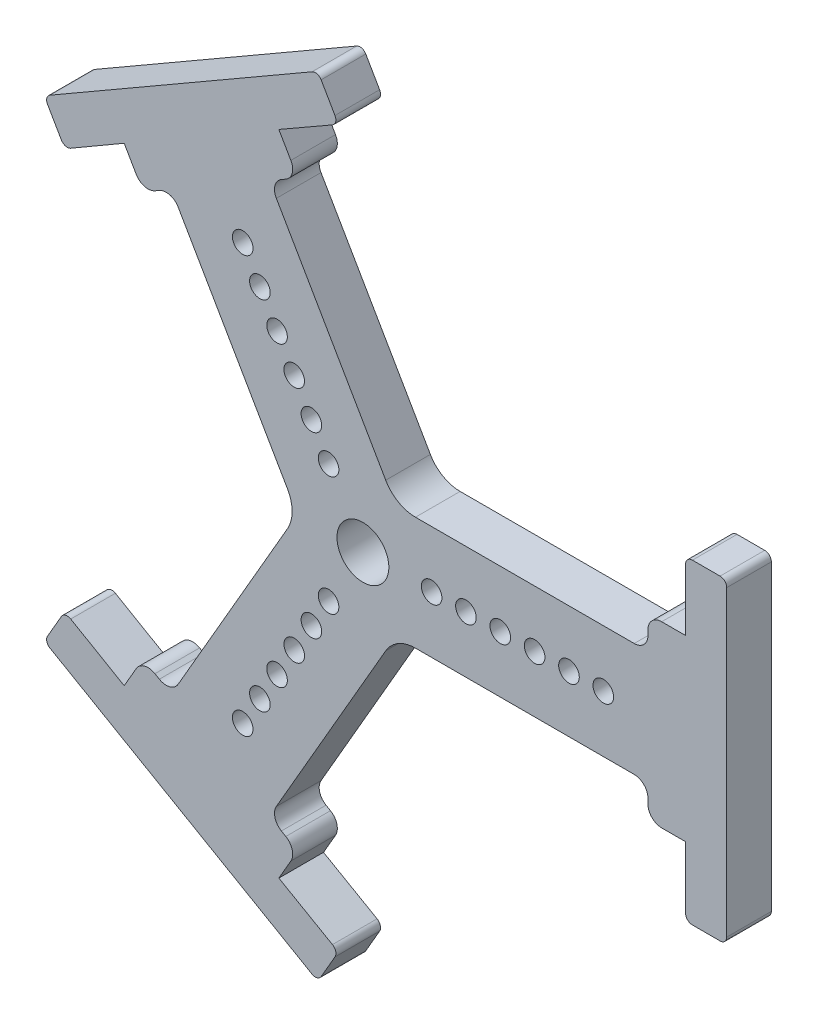
SolidWorks part; units mm, degrees
ref_plane "Plan de face" through (0, 0, 0) normal (0, 0, 1) x (1, 0, 0)
ref_plane "Plan de dessus" through (0, 0, 0) normal (0, 1, 0) x (1, 0, 0)
ref_plane "Plan de droite" through (0, 0, 0) normal (1, 0, 0) x (0, 0, -1)
sketch "Esquisse1" plane through (0, 0, 0) normal (0, 0, 1) x (1, 0, 0)
  line L0 (0, 0) -> (132.854, 0) construction
  line L1 (93.9876, -26) -> (93.9407, -43.9948)
  line L3 (95.9407, -46) -> (104, -46)
  line L4 (15.3045, 16.5081) -> (79, 16.5081)
  line L5 (83, 20.5081) -> (83, 22)
  line L6 (87, 26) -> (93.9876, 26)
  line L13 (87, -26) -> (93.9876, -26)
  line L19 (83, -20.5081) -> (83, -22)
  line L22 (15.3045, -16.5081) -> (79, -16.5081)
  line L28 (95.9407, 46) -> (104, 46)
  line L29 (105.9354, 44.0646) -> (105.9354, -44.0646)
  line L31 (93.9876, 26) -> (93.9407, 43.9948)
  line L32 (6.6442, -21.5081) -> (-25.2036, -76.6701)
  line L33 (-20.9833, -88.3442) -> (-24.4772, -94.3957)
  line L34 (-24.4772, -94.3957) -> (-8.8697, -103.3524)
  line L35 (-8.1332, -106.0871) -> (-12.1628, -113.0666)
  line L36 (-14.8067, -113.7751) -> (-91.1287, -69.7105)
  line L37 (-87.8075, -60.0871) -> (-91.8372, -67.0666)
  line L38 (-69.5105, -68.3957) -> (-85.0709, -59.3576)
  line L39 (-66.0167, -62.3442) -> (-69.5105, -68.3957)
  line L40 (-59.2605, -61.6261) -> (-60.5526, -60.8801)
  line L41 (-21.9486, -5) -> (-53.7964, -60.162)
  line L42 (-23.7395, -82.1342) -> (-22.4474, -82.8801)
  line L43 (-21.9486, 5) -> (-53.7964, 60.162)
  line L44 (-66.0167, 62.3442) -> (-69.5105, 68.3957)
  line L45 (-69.5105, 68.3957) -> (-85.0709, 59.3576)
  line L46 (-87.8075, 60.0871) -> (-91.8372, 67.0666)
  line L47 (-91.1287, 69.7105) -> (-14.8067, 113.7751)
  line L48 (-8.1332, 106.0871) -> (-12.1628, 113.0666)
  line L49 (-24.4772, 94.3957) -> (-8.8697, 103.3524)
  line L50 (-20.9833, 88.3442) -> (-24.4772, 94.3957)
  line L51 (-23.7395, 82.1342) -> (-22.4474, 82.8801)
  line L52 (6.6442, 21.5081) -> (-25.2036, 76.6701)
  line L53 (-59.2605, 61.6261) -> (-60.5526, 60.8801)
  circle A1 centre (0, 0) radius 7.55
  arc A3 (83, 22) -> (87, 26) centre (87, 22) cw
  arc A4 (79, 16.5081) -> (83, 20.5081) centre (79, 20.5081) ccw
  circle A15 centre (20, 0) radius 3
  circle A16 centre (40, 0) radius 3
  circle A17 centre (60, 0) radius 3
  circle A18 centre (70, 0) radius 3
  circle A19 centre (50, 0) radius 3
  circle A20 centre (30, 0) radius 3
  arc A33 (15.3045, 16.5081) -> (6.6442, 21.5081) centre (15.3045, 26.5081) cw
  arc A36 (95.9407, 46) -> (93.9407, 43.9948) centre (95.9407, 44) ccw
  arc A37 (105.9354, -44.0646) -> (104, -46) centre (104, -44.0646) cw
  arc A38 (95.9407, -46) -> (93.9407, -43.9948) centre (95.9407, -44) cw
  arc A39 (105.9354, 44.0646) -> (104, 46) centre (104, 44.0646) ccw
  arc A40 (79, -16.5081) -> (83, -20.5081) centre (79, -20.5081) cw
  arc A41 (83, -22) -> (87, -26) centre (87, -22) ccw
  arc A42 (15.3045, -16.5081) -> (6.6442, -21.5081) centre (15.3045, -26.5081) ccw
  arc A43 (6.6442, -21.5081) -> (15.3045, -16.5081) centre (15.3045, -26.5081) cw
  arc A44 (-25.2036, -76.6701) -> (-23.7395, -82.1342) centre (-21.7395, -78.6701) ccw
  arc A45 (-22.4474, -82.8801) -> (-20.9833, -88.3442) centre (-24.4474, -86.3442) cw
  arc A46 (-8.1332, -106.0871) -> (-8.8697, -103.3524) centre (-9.8652, -105.0871) ccw
  arc A47 (-14.8067, -113.7751) -> (-12.1628, -113.0666) centre (-13.839, -112.0989) ccw
  arc A48 (-60.5526, -60.8801) -> (-66.0167, -62.3442) centre (-62.5526, -64.3442) ccw
  arc A49 (-53.7964, -60.162) -> (-59.2605, -61.6261) centre (-57.2605, -58.162) cw
  circle A50 centre (-35, -60.6218) radius 3
  circle A51 centre (-30, -51.9615) radius 3
  circle A52 centre (-25, -43.3013) radius 3
  circle A53 centre (-15, -25.9808) radius 3
  circle A54 centre (-10, -17.3205) radius 3
  circle A55 centre (-20, -34.641) radius 3
  arc A56 (-21.9486, 5) -> (-21.9486, -5) centre (-30.6089, 0) cw
  arc A57 (-53.7964, 60.162) -> (-59.2605, 61.6261) centre (-57.2605, 58.162) ccw
  arc A58 (-60.5526, 60.8801) -> (-66.0167, 62.3442) centre (-62.5526, 64.3442) cw
  arc A59 (-87.8075, 60.0871) -> (-85.0709, 59.3576) centre (-86.0755, 61.0871) ccw
  arc A60 (-91.1287, 69.7105) -> (-91.8372, 67.0666) centre (-90.161, 68.0344) ccw
  arc A61 (-22.4474, 82.8801) -> (-20.9833, 88.3442) centre (-24.4474, 86.3442) ccw
  arc A62 (-25.2036, 76.6701) -> (-23.7395, 82.1342) centre (-21.7395, 78.6701) cw
  circle A63 centre (-35, 60.6218) radius 3
  circle A64 centre (-30, 51.9615) radius 3
  circle A65 centre (-25, 43.3013) radius 3
  circle A66 centre (-15, 25.9808) radius 3
  circle A67 centre (-10, 17.3205) radius 3
  circle A68 centre (-20, 34.641) radius 3
  arc A69 (-87.8075, -60.0871) -> (-85.0709, -59.3576) centre (-86.0755, -61.0871) cw
  arc A70 (-91.1287, -69.7105) -> (-91.8372, -67.0666) centre (-90.161, -68.0344) cw
  arc A71 (-8.1332, 106.0871) -> (-8.8697, 103.3524) centre (-9.8652, 105.0871) cw
  arc A72 (-14.8067, 113.7751) -> (-12.1628, 113.0666) centre (-13.839, 112.0989) cw
  point P7 (90.4938, 26)
  point P9 (83, 21.254)
  point P15 (83, 26)
  point P36 (105.9354, 0)
  point P38 (105.9354, -46)
  point P39 (93.9354, -46)
  point P40 (83, -26)
  point P66 (0, 0)
  point P79 (-92.8049, -68.7428)
  point P80 (-86.8049, -58.3505)
  point P110 (93.9354, 46)
  point P118 (105.9354, 46)
  point P128 (-13.1306, 114.7428)
  point P129 (-7.1306, 104.3505)
  point P146 (0, 0)
  dimension "D10" = 4
  dimension "D11" = 4
  dimension "D13" = 6
  dimension "D14" = 6
  dimension "D15" = 6
  dimension "D16" = 6
  dimension "D18" = 6
  dimension "D30" = 2
  dimension "D6" = 6
  dimension "D12" = 15.1
  dimension "D19" = 10
  dimension "D20" = 10
  dimension "D21" = 10
  dimension "D22" = 10
  dimension "D23" = 10
  dimension "D29" = 12
  dimension "D5" = 11
  dimension "D8" = 46
  dimension "D4" = 20
  dimension "D7" = 16.5081
  dimension "D9" = 26
  dimension "D17" = 105.9354
  dimension "D24" = 3
extrude "Boss.-Extru.1" add sketch "Esquisse1" along normal blind 13
equation "\"D14@Esquisse1\"=\"D13@Esquisse1\""
equation "\"D15@Esquisse1\"=\"D13@Esquisse1\""
equation "\"D16@Esquisse1\"=\"D13@Esquisse1\""
equation "\"D18@Esquisse1\"=\"D13@Esquisse1\""
equation "\"D20@Esquisse1\"=\"D19@Esquisse1\""
